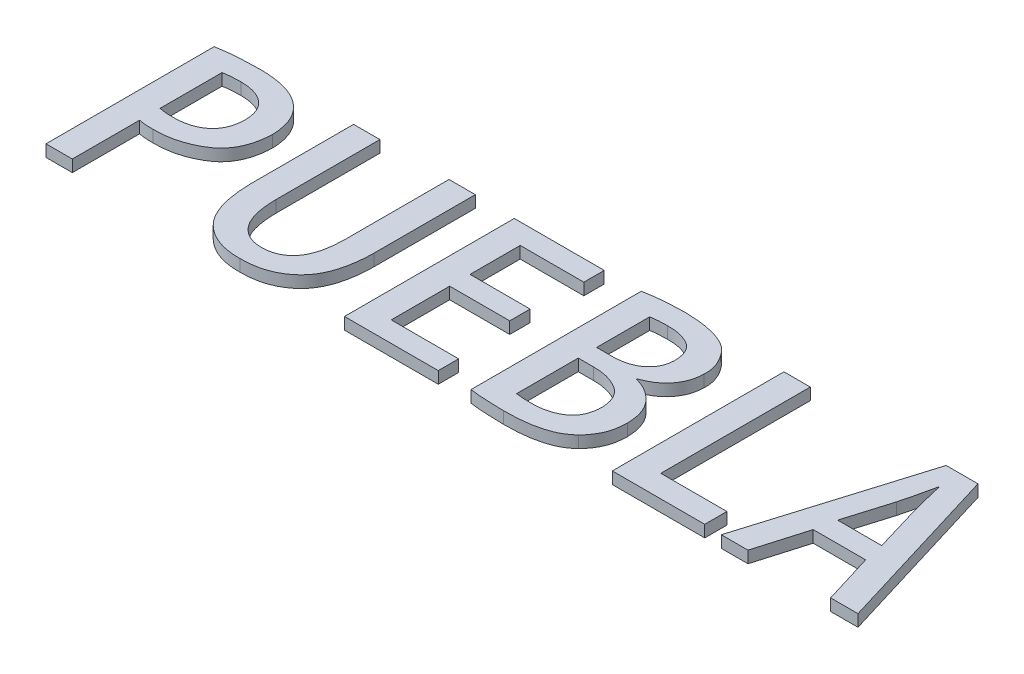
SolidWorks part; units mm, degrees
ref_plane "Alzado" through (0, 0, 0) normal (0, 0, 1) x (1, 0, 0)
ref_plane "Planta" through (0, 0, 0) normal (0, 1, 0) x (1, 0, 0)
ref_plane "Vista lateral" through (0, 0, 0) normal (1, 0, 0) x (0, 0, -1)
sketch "Croquis1" plane through (0, 0, 0) normal (0, 1, 0) x (1, 0, 0)
  line L0 (-11, -3.5898) -> (11, -3.5898) construction
  line L1 (0, 0) -> (0, -3.5898) construction
  text T0 "PUEBLA" font "@Adobe Heiti Std R" height in points 14
  dimension "D1" = 22
extrude "Saliente-Extruir1" add sketch "Croquis1" along normal blind 0.3
